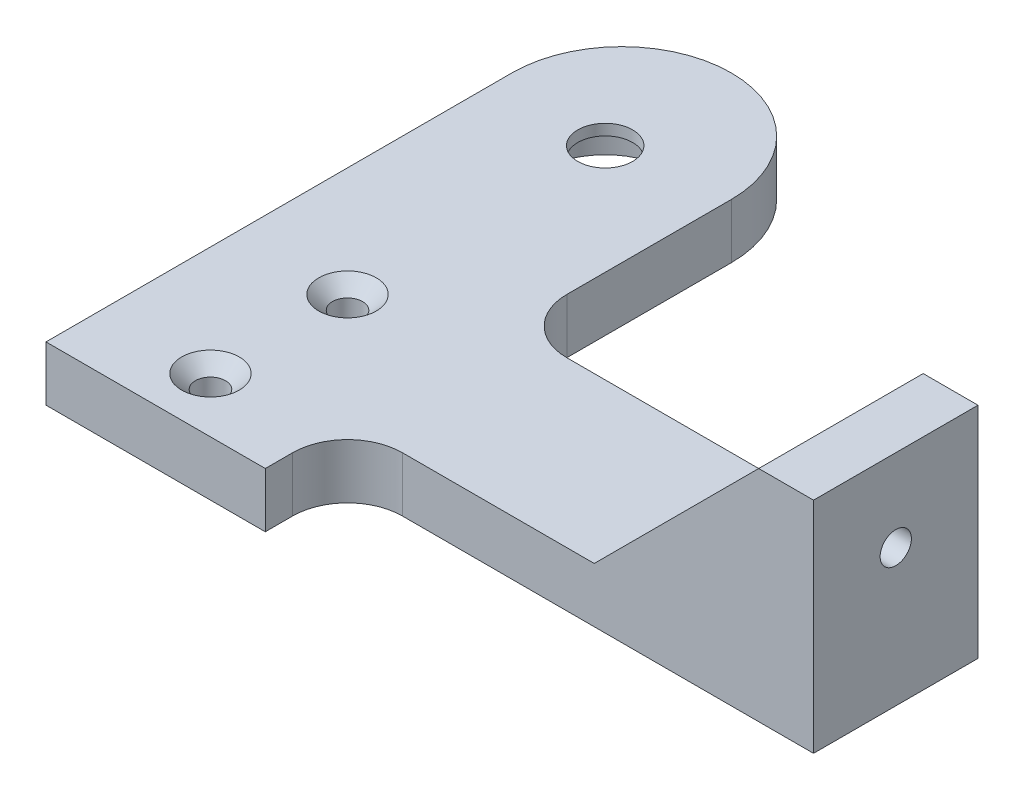
SolidWorks part; units mm, degrees
ref_plane "Front Plane" through (0, 0, 0) normal (0, 0, 1) x (1, 0, 0)
ref_plane "Top Plane" through (0, 0, 0) normal (0, 1, 0) x (1, 0, 0)
ref_plane "Right Plane" through (0, 0, 0) normal (1, 0, 0) x (0, 0, -1)
sketch "Sketch1" plane through (0, 0, 0) normal (0, 1, 0) x (1, 0, 0)
  line L1 (-20, 0) -> (20, 0)
  line L6 (-20, 85) -> (-20, 0)
  line L7 (20, 85) -> (20, 0)
  circle A2 centre (0, 10) radius 2.75
  circle A6 centre (0, 82) radius 12.1
  circle A7 centre (0, 35) radius 2.75
  arc A10 (-20, 85) -> (20, 85) centre (0, 85) cw
  point P0 (0, 0)
  dimension "D2" = 5.5
  dimension "D3" = 20
  dimension "D5" = 5.5
  dimension "D6" = 24.2
  dimension "D9" = 0
  dimension "D8" = 3
  dimension "D1" = 40
  dimension "D7" = 10
  dimension "D4" = 25
  dimension "D10" = 47
extrude "Boss-Extrude1" add sketch "Sketch1" along normal blind 8
sketch "Sketch3" plane through (0, 8, 0) normal (0, 1, 0) x (1, 0, 0)
  line L0 (-20, 0) -> (20, 0)
  line L1 (20, 0) -> (20, 85)
  line L3 (-20, 85) -> (-20, 0) construction
  line L4 (-20, 85) -> (-20, 0)
  arc A0 (20, 85) -> (-20, 85) centre (0, 85) ccw construction
  arc A1 (-20, 85) -> (20, 85) centre (0, 85) cw
  circle A2 centre (0, 10) radius 2.75
  circle A3 centre (0, 35) radius 2.75
  circle A4 centre (0, 82) radius 5
  dimension "D1" = 10
extrude "Boss-Extrude3" add sketch "Sketch3" along normal blind 2
ref_plane "Plane1" through (0, 0, -30) normal (0, 0, 1) x (1, 0, 0)
sketch "Sketch4" plane through (0, 0, -30) normal (0, 0, 1) x (1, 0, 0)
  line L0 (20, 0) -> (105, 0)
  line L1 (105, 0) -> (105, 40)
  line L2 (105, 40) -> (95, 40)
  line L3 (95, 40) -> (95, 13.5355)
  line L4 (95, 13.5355) -> (91.4645, 10)
  line L5 (91.4645, 10) -> (20, 10)
  line L6 (20, 10) -> (20, 0) construction
  line L7 (20, 10) -> (20, 0)
  dimension "D1" = 85
  dimension "D2" = 10
  dimension "D3" = 135
  dimension "D4" = 40
  dimension "D5" = 10
  dimension "D6" = 5
extrude "Boss-Extrude4" add sketch "Sketch4" along normal mid plane 30
fillet "Fillet1" radius 10 2 edges at (20, 5, -45) (20, 5, -15)
sketch "Sketch5" plane through (105, 0, 0) normal (1, 0, 0) x (0, 0, -1)
  line L0 (30, 5.5) -> (30, -5.5) construction
  line L2 (15, 40) -> (45, 40) construction
  circle A0 centre (30, 25) radius 2.85
  dimension "D1" = 5.7
  dimension "D2" = 15
extrude "Cut-Extrude1" cut sketch "Sketch5" against normal blind 40
sketch "Sketch6" plane through (0, 0, -15) normal (0, 0, 1) x (1, 0, 0)
  line L5 (65, 10) -> (95, 10)
  line L6 (91.4645, 10) -> (30, 10) construction
  line L7 (95, 10) -> (95, 40)
  line L8 (95, 40) -> (95, 13.5355) construction
  line L9 (95, 40) -> (65, 10)
  dimension "D1" = 30
  dimension "D2" = 90
  dimension "D3" = 45
extrude "Boss-Extrude5" add sketch "Sketch6" against normal blind 5 contours L5 L7 L9
mirror "Mirror1" about plane through (0, 0, -30) normal (0, 0, 1) of "Boss-Extrude5"
chamfer "Chamfer1" distance 2.5 angle 45 2 edges at (0, 10, -32.25) (0, 10, -7.25)
